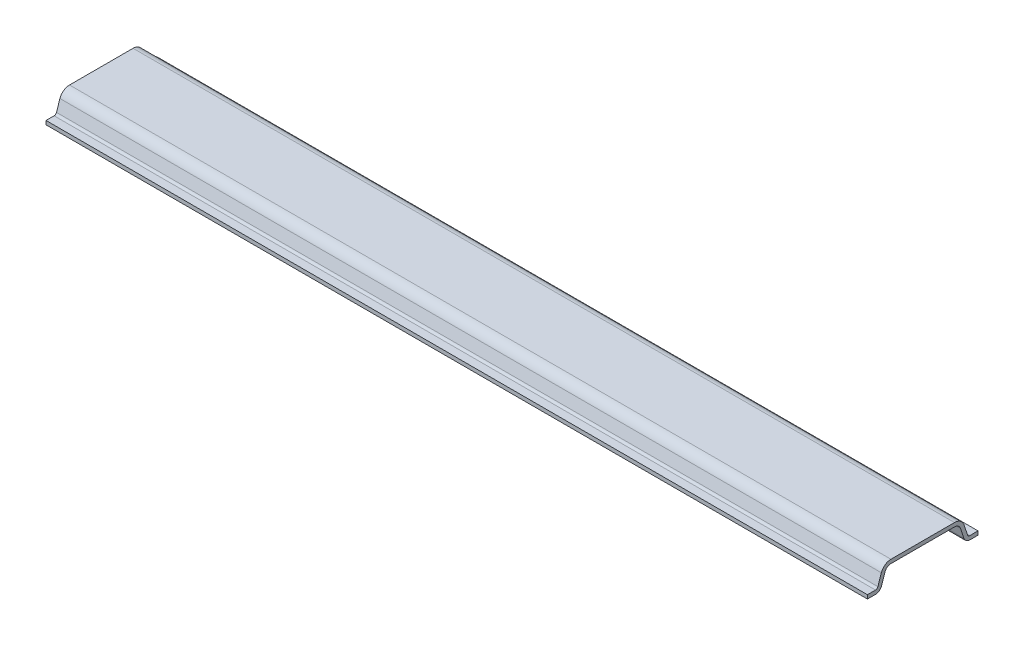
SolidWorks part; units mm, degrees
material "延性铁"
ref_plane "前视基准面" through (0, 0, 0) normal (0, 0, 1) x (1, 0, 0)
ref_plane "上视基准面" through (0, 0, 0) normal (0, 1, 0) x (1, 0, 0)
ref_plane "右视基准面" through (0, 0, 0) normal (1, 0, 0) x (0, 0, -1)
sketch "草图1" plane through (0, 0, 0) normal (1, 0, 0) x (0, 0, -1)
  line L0 (17.5, 0) -> (14.9415, 0)
  line L1 (13.0442, 1.3675) -> (11.9558, 4.6325)
  line L2 (10.0585, 6) -> (-10.0585, 6)
  line L3 (17.5, 1.2) -> (14.9415, 1.2)
  line L4 (0, 6) -> (0, 0) construction
  line L5 (-13.0442, 1.3675) -> (-11.9558, 4.6325)
  line L6 (-17.5, 0) -> (-14.9415, 0)
  line L7 (14.1826, 1.747) -> (13.0943, 5.0119)
  line L8 (10.0585, 7.2) -> (-10.0585, 7.2)
  line L9 (-14.1826, 1.747) -> (-13.0943, 5.0119)
  line L10 (-17.5, 1.2) -> (-14.9415, 1.2)
  line L11 (-17.5, 1.2) -> (-17.5, 0)
  line L12 (17.5, 1.2) -> (17.5, 0)
  arc A0 (11.9558, 4.6325) -> (10.0585, 6) centre (10.0585, 4) ccw
  arc A1 (14.9415, 0) -> (13.0442, 1.3675) centre (14.9415, 2) cw
  arc A2 (-14.9415, 0) -> (-13.0442, 1.3675) centre (-14.9415, 2) ccw
  arc A3 (-11.9558, 4.6325) -> (-10.0585, 6) centre (-10.0585, 4) cw
  arc A4 (14.9415, 1.2) -> (14.1826, 1.747) centre (14.9415, 2) cw
  arc A5 (13.0943, 5.0119) -> (10.0585, 7.2) centre (10.0585, 4) ccw
  arc A6 (-13.0943, 5.0119) -> (-10.0585, 7.2) centre (-10.0585, 4) cw
  arc A7 (-14.9415, 1.2) -> (-14.1826, 1.747) centre (-14.9415, 2) ccw
  point P10 (11.5, 6)
  point P13 (13.5, 0)
  point P21 (-13.5, 0)
  point P22 (-11.5, 6)
  dimension "D5" = 2
  dimension "D1" = 35
  dimension "D2" = 6
  dimension "D3" = 11.5
  dimension "D4" = 4
  dimension "D6" = 1.2
extrude "凸台-拉伸1" add sketch "草图1" along normal mid plane 260
